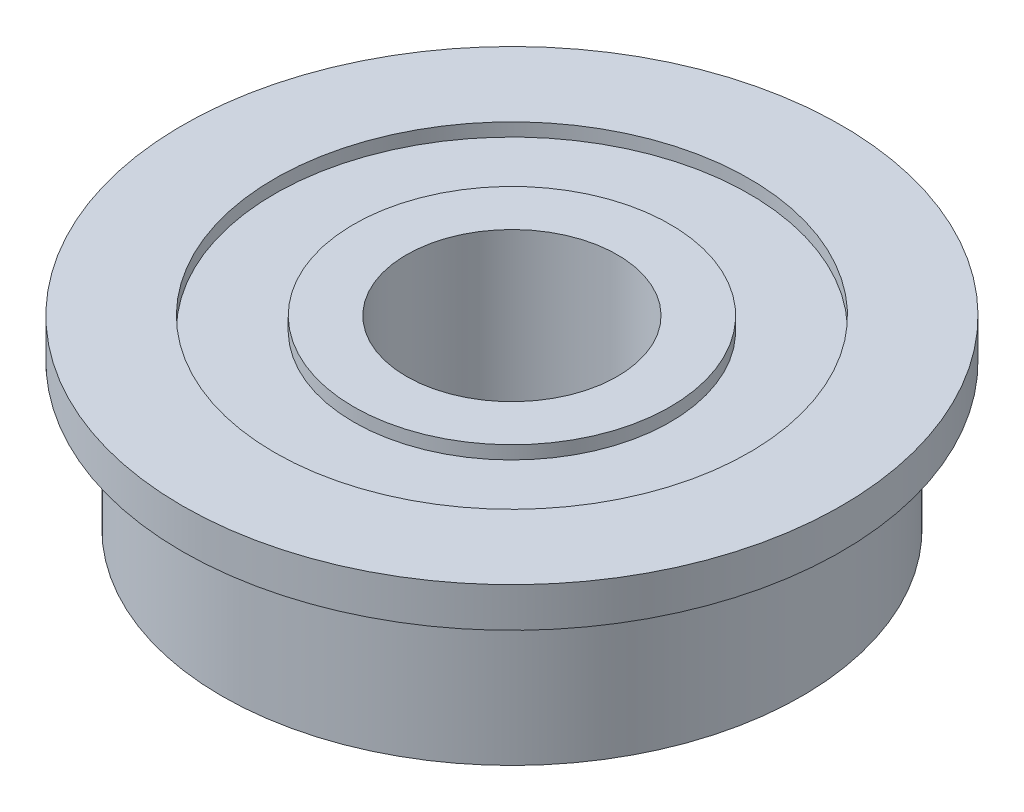
SolidWorks part; units mm, degrees
ref_plane "Front Plane" through (0, 0, 0) normal (0, 0, 1) x (1, 0, 0)
ref_plane "Top Plane" through (0, 0, 0) normal (0, 1, 0) x (1, 0, 0)
ref_plane "Right Plane" through (0, 0, 0) normal (1, 0, 0) x (0, 0, -1)
sketch "Sketch1" plane through (0, 0, 0) normal (0, 1, 0) x (1, 0, 0)
  circle A0 centre (0, 0) radius 11
  circle A1 centre (0, 0) radius 4
  dimension "D1" = 22
  dimension "D2" = 8
extrude "Boss-Extrude1" add sketch "Sketch1" along normal blind 5.5
sketch "Sketch2" plane through (0, 5.5, 0) normal (0, 1, 0) x (1, 0, 0)
  circle A0 centre (0, 0) radius 12.5
  circle A1 centre (0, 0) radius 4 construction
  circle A2 centre (0, 0) radius 4
  dimension "D1" = 25
extrude "Boss-Extrude2" add sketch "Sketch2" along normal blind 1.5
sketch "Sketch3" plane through (0, 7, 0) normal (0, 1, 0) x (1, 0, 0)
  circle A0 centre (0, 0) radius 6
  circle A1 centre (0, 0) radius 9
  dimension "D1" = 12
  dimension "D2" = 18
extrude "Cut-Extrude1" cut sketch "Sketch3" against normal blind 0.5
sketch "Sketch4" plane through (0, 0, 0) normal (0, -1, 0) x (1, 0, 0)
  circle A0 centre (0, 0) radius 6
  circle A1 centre (0, 0) radius 9
  dimension "D1" = 12
  dimension "D2" = 18
extrude "Cut-Extrude2" cut sketch "Sketch4" against normal blind 0.5
